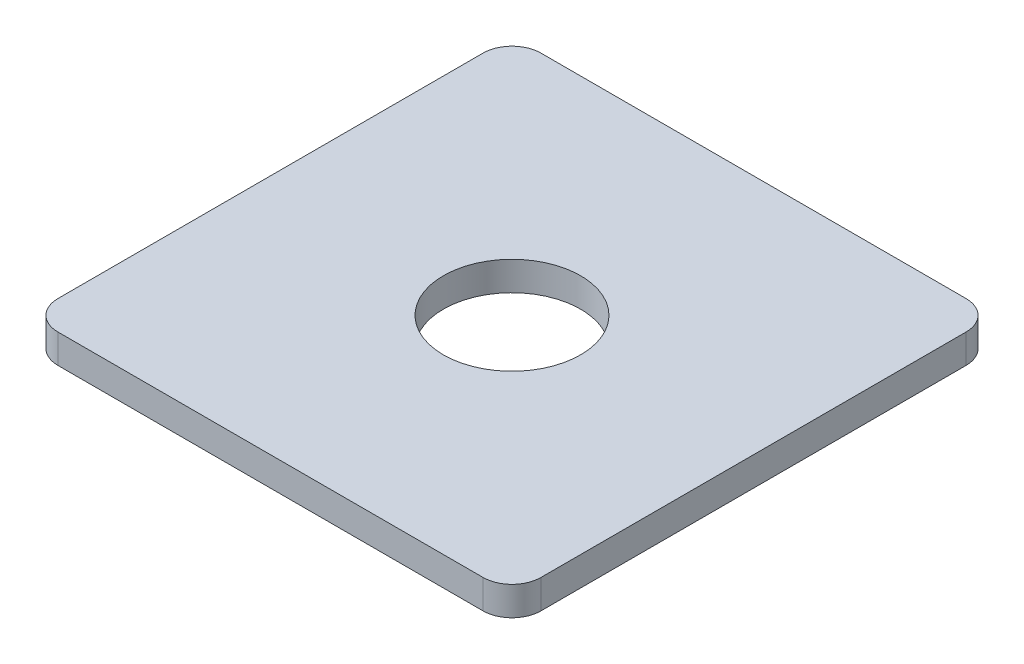
SolidWorks part; units mm, degrees
ref_plane "前视基准面" through (0, 0, 0) normal (0, 0, 1) x (1, 0, 0)
ref_plane "上视基准面" through (0, 0, 0) normal (0, 1, 0) x (1, 0, 0)
ref_plane "右视基准面" through (0, 0, 0) normal (1, 0, 0) x (0, 0, -1)
other "Configuration Table"
sketch "草图1" plane through (0, 0, 0) normal (0, 0, 1) x (1, 0, 0)
  line L0 (0, 0) -> (50, 0)
  line L1 (50, 0) -> (50, 3)
  line L2 (50, 3) -> (0, 3)
  line L3 (0, 3) -> (0, 0)
  dimension "width" = 50
  dimension "height" = 3
extrude "BlockExtrude" add sketch "草图1" along normal blind 50
fillet "Fillet" radius 3 4 edges at (0, 1.5, 0) (50, 1.5, 0) (0, 1.5, 50) (50, 1.5, 50)
sketch "草图2" plane through (0, 3, 0) normal (0, 1, 0) x (1, 0, 0)
  circle A0 centre (25, -25) radius 7.1
  dimension "diameter" = 14.2
  dimension "x" = 25
  dimension "y" = 25
extrude "Coaxial_feedthrough" cut sketch "草图2" against normal through all
